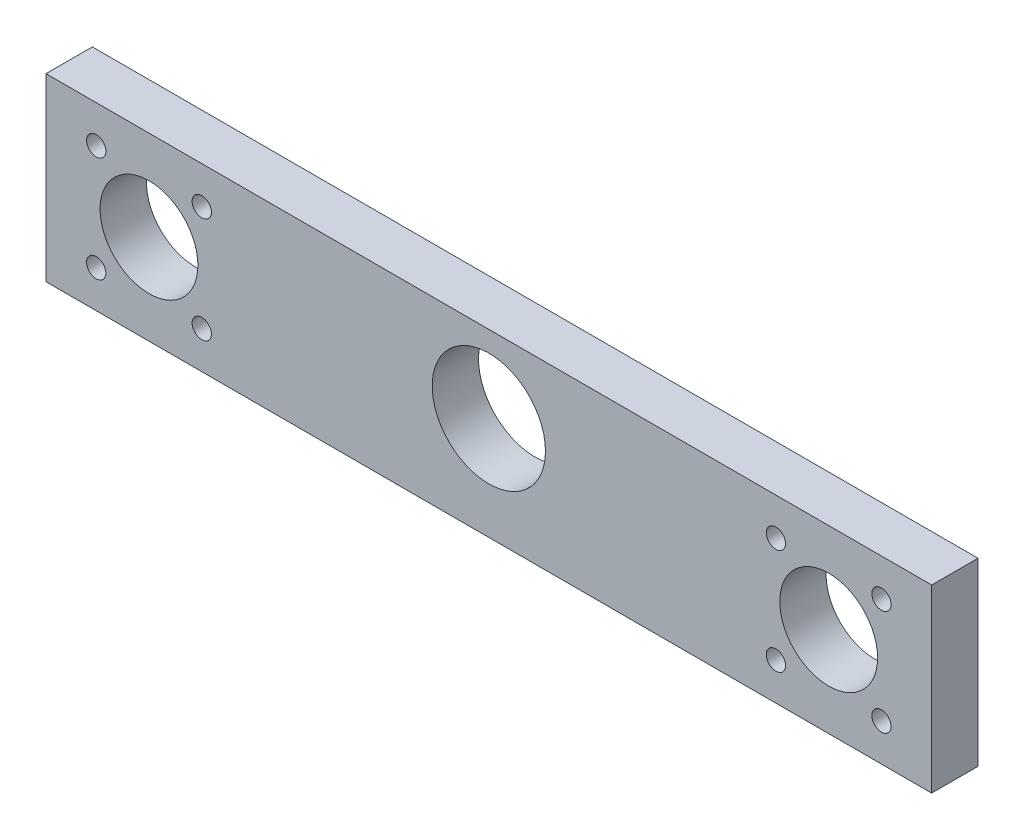
SolidWorks part; units mm, degrees
material "1060 Alloy"
ref_plane "Front Plane" through (0, 0, 0) normal (0, 0, 1) x (1, 0, 0)
ref_plane "Top Plane" through (0, 0, 0) normal (0, 1, 0) x (1, 0, 0)
ref_plane "Right Plane" through (0, 0, 0) normal (1, 0, 0) x (0, 0, -1)
sketch "Sketch1" plane through (0, 0, 0) normal (0, 0, 1) x (1, 0, 0)
  line L1 (0, 0) -> (172, 0)
  line L2 (0, 0) -> (0, 35)
  line L3 (0, 35) -> (172, 35)
  line L4 (172, 0) -> (172, 35)
  dimension "D1" = 35
  dimension "D2" = 172
extrude "Boss-Extrude1" add sketch "Sketch1" along normal blind 9
sketch "Sketch2" plane through (0, 0, 9) normal (0, 0, 1) x (1, 0, 0)
  line L0 (172, 35) -> (0, 35) construction
  line L1 (0, 35) -> (0, 0) construction
  line L2 (172, 0) -> (172, 35) construction
  line L3 (86, 35) -> (86, 0) construction
  line L4 (0, 0) -> (172, 0) construction
  circle A0 centre (9.75, 27.75) radius 1.875
  circle A1 centre (30.25, 27.75) radius 1.875
  circle A2 centre (9.75, 7.25) radius 1.875
  circle A3 centre (30.25, 7.25) radius 1.875
  circle A4 centre (141.75, 27.75) radius 1.875
  circle A5 centre (162.25, 27.75) radius 1.875
  circle A6 centre (141.75, 7.25) radius 1.875
  circle A7 centre (162.25, 7.25) radius 1.875
  circle A8 centre (20, 17.5) radius 9.5
  circle A9 centre (152, 17.5) radius 9.5
  circle A10 centre (86, 20) radius 11
  dimension "D7" = 3.75
  dimension "D10" = 19
  dimension "D12" = 22
  dimension "D1" = 7.25
  dimension "D2" = 20.5
  dimension "D3" = 9.75
  dimension "D4" = 9.75
  dimension "D5" = 20.5
  dimension "D6" = 20.5
  dimension "D8" = 20
  dimension "D9" = 17.5
  dimension "D11" = 20
  dimension "D13" = 15
extrude "Cut-Extrude1" cut sketch "Sketch2" against normal through all
